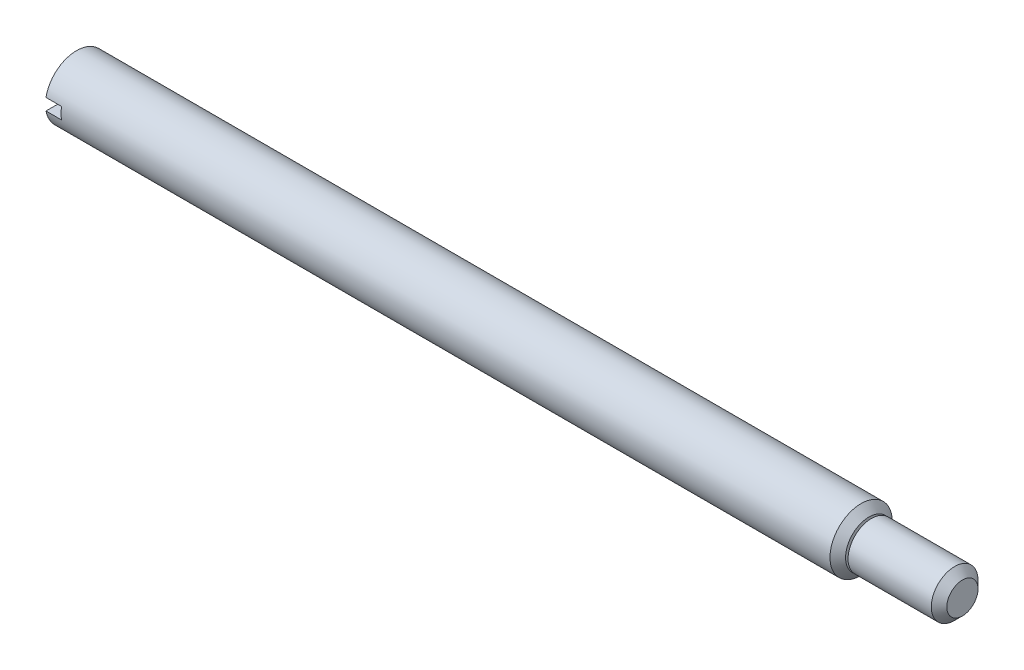
SolidWorks part; units mm, degrees
ref_plane "Plane1" through (0, 0, 0) normal (0, 0, 1) x (1, 0, 0)
ref_plane "Plane2" through (0, 0, 0) normal (0, 1, 0) x (1, 0, 0)
ref_plane "Plane3" through (0, 0, 0) normal (1, 0, 0) x (0, 0, -1)
sketch "BodySke" plane through (0, 0, 0) normal (0, 0, 1) x (1, 0, 0)
  line L0 (0, 0) -> (0, 2.4455)
  line L1 (0, 2.4455) -> (0.3201, 3)
  line L2 (0.3201, 3) -> (11, 3)
  line L3 (11, 3) -> (12, 2)
  line L4 (12, 0) -> (0, 0)
  line L5 (-12.7, 0) -> (88.9, 0) construction
  line L6 (12, 2) -> (12, 0)
  line L7 (12, 2) -> (12, 11.525) construction
  line L8 (0, -2.4455) -> (0.3201, -3) construction
  line L9 (1, 15.875) -> (1, -3.175) construction
  line L10 (11, -3) -> (12, -2) construction
  dimension "Length" = 12
  dimension "Diameter" = 6
  dimension "Drive_ch_ang" = 60
  dimension "Minor_dia" = 4.891
  dimension "Cup_nose_ang" = 45
  dimension "Cup_dia" = 4
  dimension "Advance" = 1
revolve "BaseBody" add sketch "BodySke" angle 360 about L5
cosmetic thread "ThreadCosmetic" parameters "Thread_minor"=4.891
sketch "ThdSchSke" plane through (0, 0, 0) normal (0, 0, 1) x (1, 0, 0)
  line L0 (0.3201, -2.4455) -> (-0.0681, -3)
  line L1 (0.3201, -2.4455) -> (0.7084, -3)
  line L2 (0.7084, -3) -> (0.7084, -3.75)
  line L3 (-3.175, 0) -> (5.1513, 0) construction
  line L5 (0.7084, -3.75) -> (-0.0681, -3.75)
  line L6 (-0.0681, -3.75) -> (-0.0681, -3)
  line L8 (0.3201, 3) -> (0.3201, -3) construction
  dimension "Thread_minor" = 4.891
  dimension "Diameter" = 6
  dimension "SideAngle" = 55
  dimension "VeeAngle" = 70
  dimension "Overcut" = 7.5
revolve "ThreadSchematic" [suppressed] cut sketch "ThdSchSke" angle 360 about L3
pattern_linear "ThdSchPat" [suppressed]
sketch "Esboço1" plane through (0, 0, 0) normal (1, 0, 0) x (0, 0, -1)
  circle A0 centre (0, 0) radius 4
  dimension "D1" = 8
extrude "Ressalto-extrusão1" add sketch "Esboço1" against normal blind 101.7
chamfer "Chanfro1" distance 1 angle 45 1 edges at (0, 0, -4)
sketch "Esboço2" plane through (-101.7, 0, 0) normal (-1, 0, 0) x (0, 0, 1)
  line L1 (-4.2396, -0.75) -> (4.2396, -0.75)
  line L2 (-4.2396, -0.75) -> (-4.2396, 0.75)
  line L3 (-4.2396, 0.75) -> (4.2396, 0.75)
  line L4 (4.2396, -0.75) -> (4.2396, 0.75)
  line L5 (-4.2396, -0.75) -> (4.2396, 0.75) construction
  line L6 (-4.2396, 0.75) -> (4.2396, -0.75) construction
  point P0 (0, 0)
  dimension "D1" = 1.5
extrude "Corte-extrusão1" cut sketch "Esboço2" against normal blind 2
equation "\"Thread_minor@ThreadCosmetic\" = \"Minor_dia@BodySke\""
equation "\"Thread_minor@ThdSchSke\" = \"Thread_minor@ThreadCosmetic\""
equation "\"Diameter@ThdSchSke\" = \"Diameter@BodySke\""
equation "\"Overcut@ThdSchSke\" = \"Diameter@BodySke\" * 1.25"
equation "\"Num_threads@ThdSchPat\" = int( (\"Length@BodySke\" - ( ( ( \"Diameter@BodySke\" - \"Minor_dia@BodySke\" ) * 0.5 ) / tan( \"Drive_ch_ang@BodySke\" * 0.017453292 ) ) - ( ( ( \"Diameter@BodySke\" - \"Cup_dia@BodySke\" ) * 0.5 ) * tan( \"Cup_nose_ang@BodySke\" * 0.017453292 ) ) ) / \"Advance@BodySke\" + 0.999 )  + 1"
equation "\"Advance@ThdSchPat\" = (\"Length@BodySke\" - ( ( ( \"Diameter@BodySke\" - \"Minor_dia@BodySke\" ) * 0.5 ) / tan( \"Drive_ch_ang@BodySke\" * 0.017453292 ) ) - ( ( ( \"Diameter@BodySke\" - \"Cup_dia@BodySke\" ) * 0.5 ) * tan( \"Cup_nose_ang@BodySke\" * 0.017453292 ) ) ) /  (\"Num_threads@ThdSchPat\" - 1) 'relax it"
equation "' \"Num_threads@ThdSchPat\" = \"Num_threads@ThdSchPat\" - sgn( \"Num_threads@ThdSchPat\" - 1) '---chamfered tips only---"
